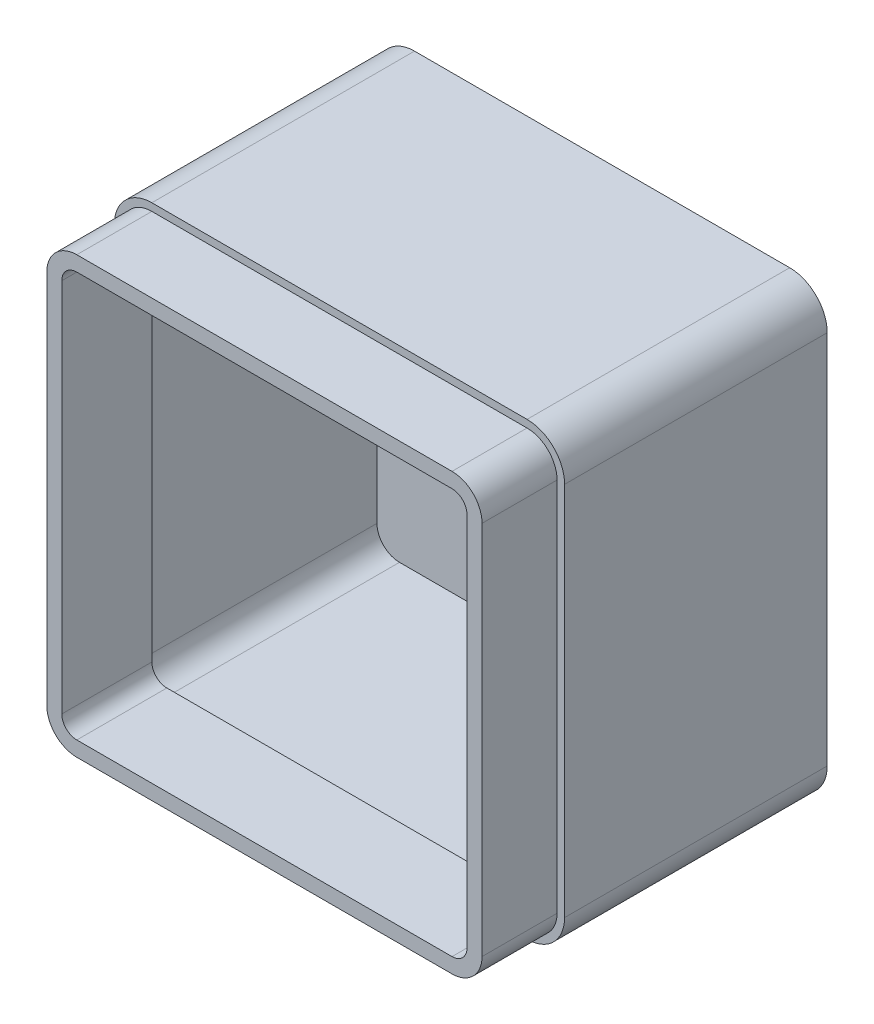
SolidWorks part; units mm, degrees
ref_plane "Front Plane" through (0, 0, 0) normal (0, 0, 1) x (1, 0, 0)
ref_plane "Top Plane" through (0, 0, 0) normal (0, 1, 0) x (1, 0, 0)
ref_plane "Right Plane" through (0, 0, 0) normal (1, 0, 0) x (0, 0, -1)
sketch "Sketch1" plane through (0, 0, 0) normal (0, 0, 1) x (1, 0, 0)
  line L1 (-60, 60) -> (60, 60)
  line L2 (-60, 60) -> (-60, -60)
  line L3 (-60, -60) -> (60, -60)
  line L4 (60, 60) -> (60, -60)
  line L5 (-60, 60) -> (60, -60) construction
  line L6 (-60, -60) -> (60, 60) construction
  point P0 (0, 0)
  dimension "D1" = 120
  dimension "D2" = 120
extrude "Boss-Extrude1" add sketch "Sketch1" along normal blind 90
fillet "Fillet1" radius 10 4 edges at (-60, -60, 45) (-60, 60, 45) (60, 60, 45) (60, -60, 45)
sketch "Sketch4" plane through (0, 0, 90) normal (0, 0, 1) x (1, 0, 0)
  line L8 (-60, 50) -> (-60, -50)
  line L9 (-50, -60) -> (50, -60)
  line L10 (60, -50) -> (60, 50)
  line L11 (50, 60) -> (-50, 60)
  line L32 (-60, 50) -> (-60, -50)
  line L33 (-50, -60) -> (50, -60)
  line L34 (60, -50) -> (60, 50)
  line L35 (50, 60) -> (-50, 60)
  line L40 (-58, 50) -> (-58, -50)
  line L41 (-50, -58) -> (50, -58)
  line L42 (58, -50) -> (58, 50)
  line L43 (50, 58) -> (-50, 58)
  line L44 (-58, 50) -> (-58, -50)
  line L45 (-50, -58) -> (50, -58)
  line L46 (58, -50) -> (58, 50)
  line L47 (50, 58) -> (-50, 58)
  arc A8 (-60, -50) -> (-50, -60) centre (-50, -50) ccw
  arc A9 (50, -60) -> (60, -50) centre (50, -50) ccw
  arc A10 (60, 50) -> (50, 60) centre (50, 50) ccw
  arc A11 (-50, 60) -> (-60, 50) centre (-50, 50) ccw
  arc A32 (-60, -50) -> (-50, -60) centre (-50, -50) ccw
  arc A33 (50, -60) -> (60, -50) centre (50, -50) ccw
  arc A34 (60, 50) -> (50, 60) centre (50, 50) ccw
  arc A35 (-50, 60) -> (-60, 50) centre (-50, 50) ccw
  arc A40 (-58, -50) -> (-50, -58) centre (-50, -50) ccw
  arc A41 (50, -58) -> (58, -50) centre (50, -50) ccw
  arc A42 (58, 50) -> (50, 58) centre (50, 50) ccw
  arc A43 (-50, 58) -> (-58, 50) centre (-50, 50) ccw
  arc A44 (-58, -50) -> (-50, -58) centre (-50, -50) ccw
  arc A45 (50, -58) -> (58, -50) centre (50, -50) ccw
  arc A46 (58, 50) -> (50, 58) centre (50, 50) ccw
  arc A47 (-50, 58) -> (-58, 50) centre (-50, 50) ccw
  dimension "D1" = 0
  dimension "D2" = 2
extrude "Cut-Extrude4" cut sketch "Sketch4" against normal blind 20
shell "Shell1" thickness 4
